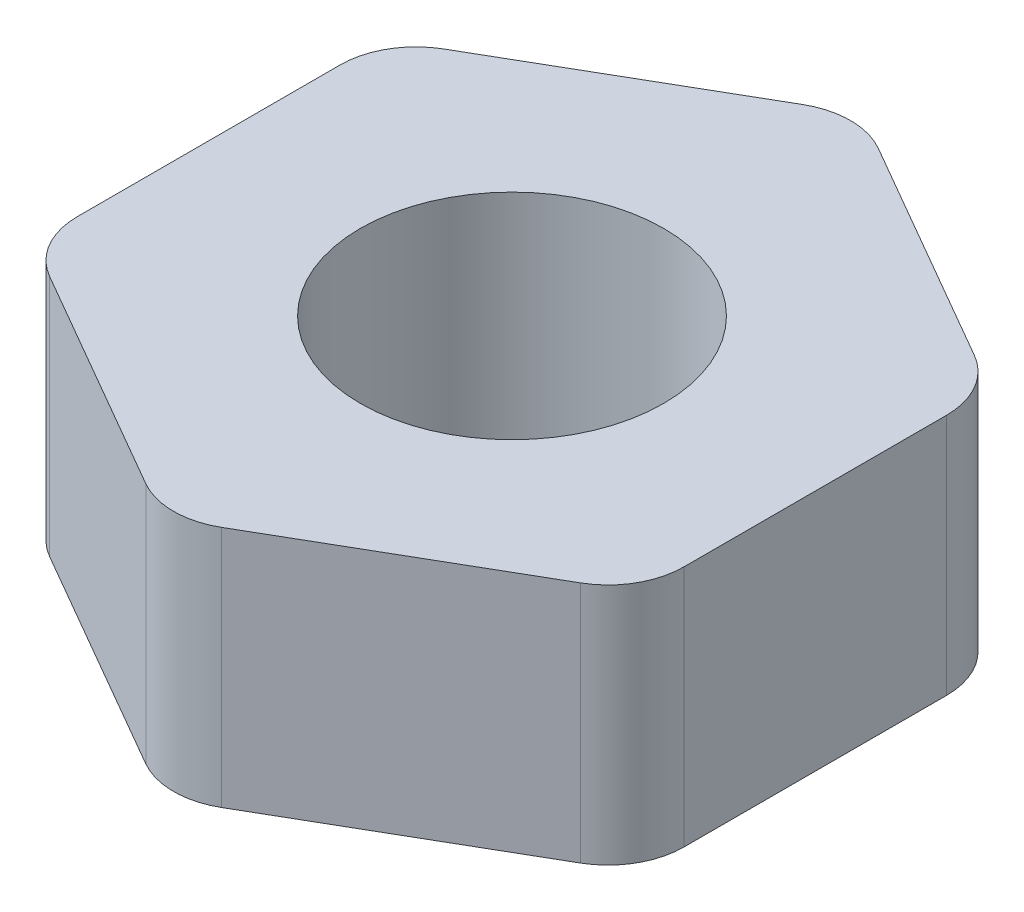
SolidWorks part; units mm, degrees
ref_plane "前视基准面" through (0, 0, 0) normal (0, 0, 1) x (1, 0, 0)
ref_plane "上视基准面" through (0, 0, 0) normal (0, 1, 0) x (1, 0, 0)
ref_plane "右视基准面" through (0, 0, 0) normal (1, 0, 0) x (0, 0, -1)
sketch "草图1" plane through (0, 0, 0) normal (0, 1, 0) x (1, 0, 0)
  line L1 (0, 2.3094) -> (-2, 1.1547)
  line L2 (-2, 1.1547) -> (-2, -1.1547)
  line L3 (-2, -1.1547) -> (0, -2.3094)
  line L4 (0, -2.3094) -> (2, -1.1547)
  line L5 (2, -1.1547) -> (2, 1.1547)
  line L6 (2, 1.1547) -> (0, 2.3094)
  circle A0 centre (0, 0) radius 2 construction
  circle A1 centre (0, 0) radius 1
  dimension "D2" = 2
  dimension "D1" = 4
extrude "凸台-拉伸1" add sketch "草图1" along normal blind 1.6
fillet "圆角1" radius 0.5 6 edges at (0, 0.8, 2.3094) (2, 0.8, 1.1547) (0, 0.8, -2.3094) (2, 0.8, -1.1547) (-2, 0.8, -1.1547) (-2, 0.8, 1.1547)
